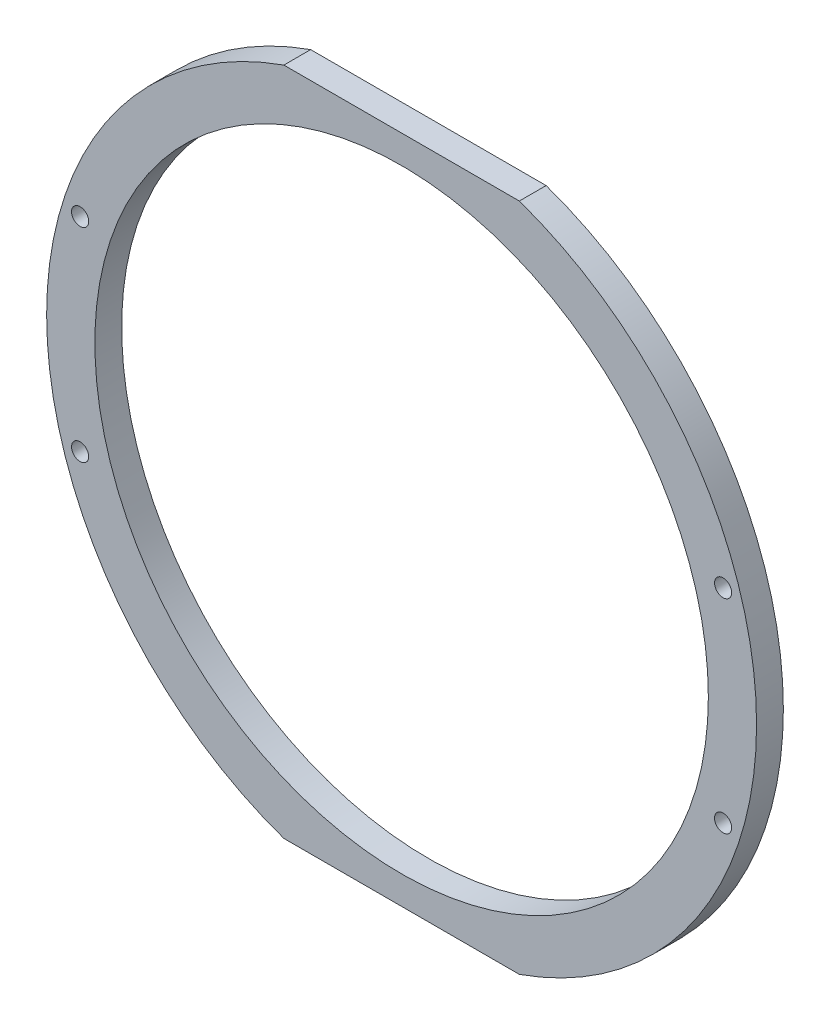
SolidWorks part; units mm, degrees
ref_plane "Plan de face" through (0, 0, 0) normal (0, 0, 1) x (1, 0, 0)
ref_plane "Plan de dessus" through (0, 0, 0) normal (0, 1, 0) x (1, 0, 0)
ref_plane "Plan de droite" through (0, 0, 0) normal (1, 0, 0) x (0, 0, -1)
sketch "Esquisse2" plane through (0, 0, 0) normal (0, 0, 1) x (1, 0, 0)
  line L0 (-21.973, 62.5) -> (21.973, 62.5)
  line L1 (0, 0) -> (66.25, 0) construction
  line L2 (-21.973, -62.5) -> (21.973, -62.5)
  line L3 (0, 0) -> (0, 62.5) construction
  circle A0 centre (60, 19) radius 1.6
  circle A1 centre (60, -19) radius 1.6
  circle A2 centre (-60, -19) radius 1.6
  circle A3 centre (-60, 19) radius 1.6
  circle A4 centre (0, 0) radius 66.25 construction
  circle A5 centre (0, 0) radius 57.25
  arc A6 (-21.973, 62.5) -> (-21.973, -62.5) centre (0, 0) ccw
  arc A7 (21.973, 62.5) -> (21.973, -62.5) centre (0, 0) cw
  dimension "D3" = 114.5
  dimension "D4" = 66.25
  dimension "D6" = 3.2
  dimension "D7" = 9
  dimension "D1" = 120
  dimension "D2" = 125
  dimension "D5" = 19
extrude "Boss.-Extru.2" add sketch "Esquisse2" along normal blind 5
